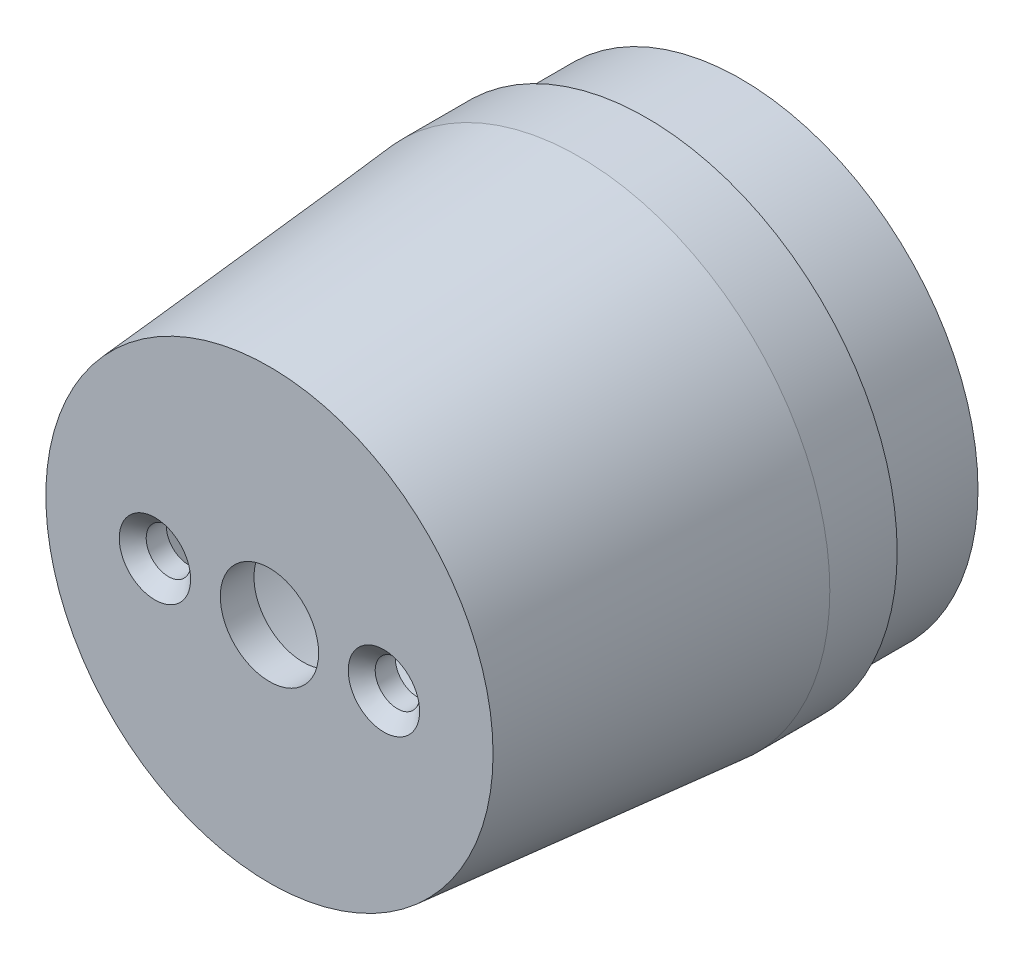
SolidWorks part; units mm, degrees
ref_plane "Спереди" through (0, 0, 0) normal (0, 0, 1) x (1, 0, 0)
ref_plane "Сверху" through (0, 0, 0) normal (0, 1, 0) x (1, 0, 0)
ref_plane "Справа" through (0, 0, 0) normal (1, 0, 0) x (0, 0, -1)
sketch "Sketch1" plane through (0, 0, 0) normal (1, 0, 0) x (0, 0, -1)
  line L0 (-7.5, 12.7) -> (25, 12.7)
  line L1 (-10, 18.6) -> (18, 18.6)
  line L2 (-10, 3.65) -> (-10, 0) construction
  line L3 (-10, 0) -> (0, 0) construction
  line L4 (-10, 18.6) -> (-10, 3.65)
  line L5 (-10, 3.65) -> (-7.5, 3.65)
  line L6 (25, 12.7) -> (25, 17.6)
  line L7 (25, 17.6) -> (18, 17.6)
  line L8 (18, 17.6) -> (18, 18.6)
  line L9 (0, 0) -> (25, 0) construction
  line L10 (-7.5, 3.65) -> (-7.5, 12.7)
  line L11 (25, 0) -> (25, 12.7) construction
  line L12 (-7.5, 3.65) -> (-7.5, 0) construction
  dimension "D1" = 7.5
  dimension "D2" = 1
  dimension "D3" = 7
  dimension "D4" = 2.5
  dimension "D5" = 3.65
  dimension "D6" = 18.6
  dimension "D7" = 25
  dimension "D8" = 12.7
  dimension "D9" = 4.9
revolve "Тело" add sketch "Sketch1" angle 360 about L9
sketch "Sketch2" plane through (0, 0, 10) normal (0, 0, 1) x (1, 0, 0)
  line L0 (0, 0) -> (8.5, 0) construction
  line L1 (0, 0) -> (-8.5, 0) construction
  circle A0 centre (0, 0) radius 8.5 construction
  circle A1 centre (8.5, 0) radius 1.65
  circle A2 centre (-8.5, 0) radius 1.65
  dimension "D1" = 17
  dimension "D2" = 3.3
  dimension "D3" = 3.3
extrude "Крепление к двигателю (винт с потайной головкой М3х6)" cut sketch "Sketch2" against normal blind 4.5
chamfer "Фаска 1" distance 1 angle 45 2 edges at (-6.85, 0, 10) (10.15, 0, 10)
sketch "Sketch3" plane through (0, 0, -25) normal (0, 0, -1) x (-1, 0, 0)
  line L0 (0, 0) -> (0, 15) construction
  line L2 (10.6066, -10.6066) -> (-10.6066, -10.6066) construction
  line L3 (10.6066, -10.6066) -> (10.6066, 10.6066) construction
  line L4 (10.6066, 10.6066) -> (-10.6066, 10.6066) construction
  line L5 (-10.6066, -10.6066) -> (-10.6066, 10.6066) construction
  line L6 (10.6066, -10.6066) -> (-10.6066, 10.6066) construction
  line L7 (10.6066, 10.6066) -> (-10.6066, -10.6066) construction
  circle A0 centre (0, 0) radius 15 construction
  circle A1 centre (-10.6066, 10.6066) radius 1
  circle A2 centre (10.6066, 10.6066) radius 1
  circle A3 centre (10.6066, -10.6066) radius 1
  circle A4 centre (-10.6066, -10.6066) radius 1
  point P12 (0, 0)
  point P16 (0, 0)
  dimension "D1" = 30
  dimension "D3" = 2
  dimension "D4" = 4
extrude "Отверстие под саморез М3х20" cut sketch "Sketch3" against normal blind 25
sketch "Эскиз2" plane through (0, 0, 0) normal (1, 0, 0) x (0, 0, -1)
  line L0 (-10, 18.6) -> (-10, 16.6)
  line L1 (18, 18.6) -> (-10, 18.6) construction
  line L2 (-10, 18.6) -> (-10, -18.6) construction
  line L3 (-10, 16.6) -> (13, 18.6)
  line L4 (13, 18.6) -> (-10, 18.6)
  line L5 (18, -18.6) -> (18, 18.6) construction
  line L6 (-10, 0) -> (25, 0) construction
  line L7 (25, -17.6) -> (25, 17.6) construction
  dimension "D1" = 5
  dimension "D2" = 2
revolve "срез конуса" cut sketch "Эскиз2" angle 360 about L6
